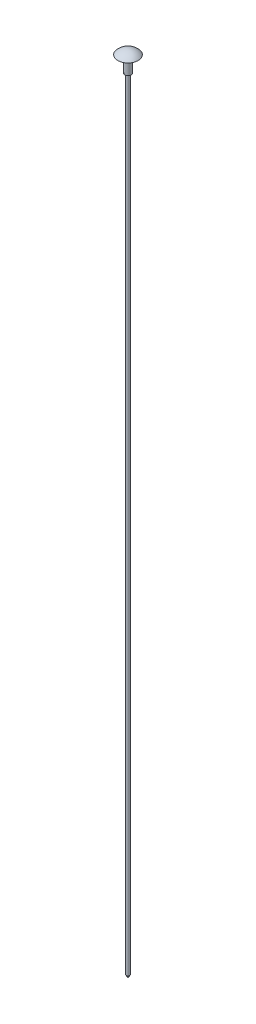
SolidWorks part; units mm, degrees
ref_plane "Front" through (0, 0, 0) normal (0, 0, 1) x (1, 0, 0)
ref_plane "Top" through (0, 0, 0) normal (0, 1, 0) x (1, 0, 0)
ref_plane "Right" through (0, 0, 0) normal (1, 0, 0) x (0, 0, -1)
sketch "Sketch1" plane through (0, 0, 0) normal (0, 0, 1) x (1, 0, 0)
  line L0 (-5.9055, 1300) -> (-5.9055, -1289.7714)
  line L1 (-5.9055, -1289.7714) -> (0, -1300)
  line L2 (0, -1300) -> (0, 1300)
  line L3 (0, 1300) -> (-5.9055, 1300) construction
  line L4 (0, 1300) -> (0, 47.9988) construction
  line L5 (0, -1300) -> (0, -1308.8652) construction
  line L6 (0, 1300) -> (0, 1535.0912) construction
  line L7 (-5.9055, 1300) -> (-10.7784, 1300)
  line L8 (-10.7784, 1300) -> (-10.7784, 1352.8877)
  line L9 (-10.7784, 1352.8877) -> (-33.7761, 1352.8877)
  line L10 (0, 1367.4568) -> (0, 1300)
  arc A0 (-33.7761, 1352.8877) -> (0, 1367.4568) centre (0, 1321.0202) cw
  dimension "D1" = 2600
  dimension "D2" = 30
  dimension "D3" = 11.811
revolve "Revolve1" add sketch "Sketch1" angle 360 about L6
